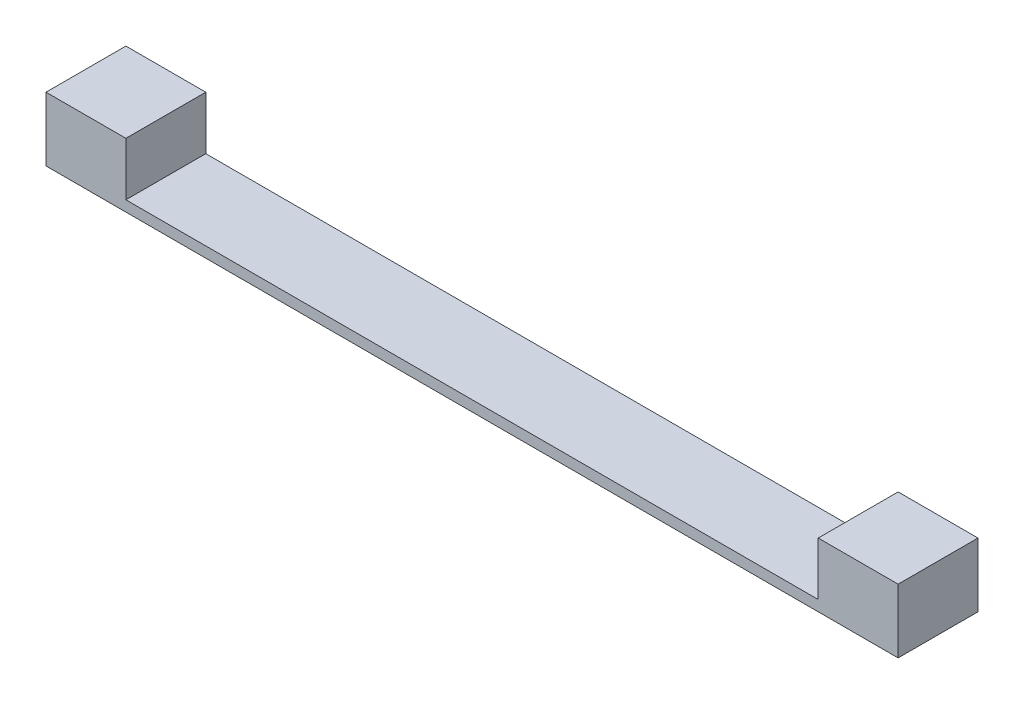
SolidWorks part; units mm, degrees
ref_plane "Front Plane" through (0, 0, 0) normal (0, 0, 1) x (1, 0, 0)
ref_plane "Top Plane" through (0, 0, 0) normal (0, 1, 0) x (1, 0, 0)
ref_plane "Right Plane" through (0, 0, 0) normal (1, 0, 0) x (0, 0, -1)
sketch "Sketch1" plane through (0, 0, 0) normal (0, 1, 0) x (1, 0, 0)
  line L1 (-40, 3.75) -> (40, 3.75)
  line L2 (-40, 3.75) -> (-40, -3.75)
  line L3 (-40, -3.75) -> (40, -3.75)
  line L4 (40, 3.75) -> (40, -3.75)
  line L5 (-40, 3.75) -> (40, -3.75) construction
  line L6 (-40, -3.75) -> (40, 3.75) construction
  point P0 (0, 0)
  dimension "D1" = 80
  dimension "D2" = 7.5
extrude "Boss-Extrude1" add sketch "Sketch1" along normal blind 1
sketch "Sketch2" plane through (0, 1, 0) normal (0, 1, 0) x (1, 0, 0)
  line L0 (-40, -3.75) -> (40, -3.75) construction
  line L1 (-40, 3.75) -> (-32.5, 3.75)
  line L2 (-40, 3.75) -> (-40, -3.75)
  line L3 (-40, -3.75) -> (-32.5, -3.75)
  line L4 (-32.5, 3.75) -> (-32.5, -3.75)
  line L6 (40, 3.75) -> (32.5, 3.75)
  line L7 (40, 3.75) -> (40, -3.75)
  line L8 (40, -3.75) -> (32.5, -3.75)
  line L9 (32.5, 3.75) -> (32.5, -3.75)
  dimension "D1" = 7.5
  dimension "D2" = 7.5
extrude "Boss-Extrude2" add sketch "Sketch2" along normal blind 5
